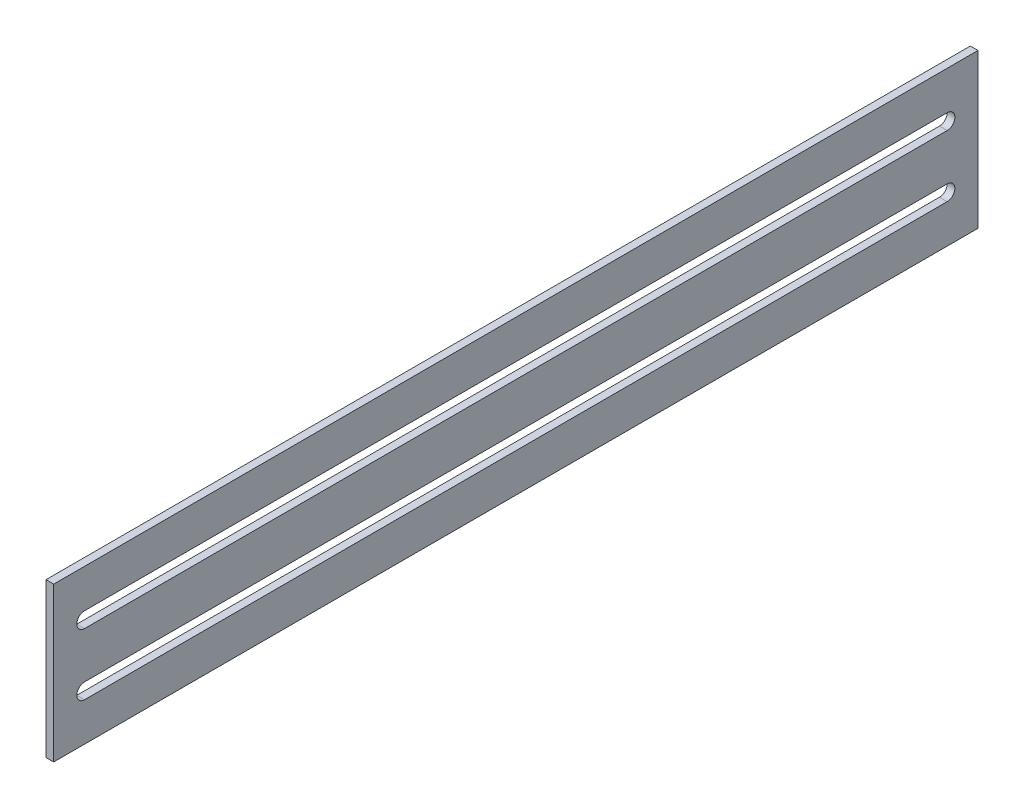
SolidWorks part; units mm, degrees
ref_plane "Front Plane" through (0, 0, 0) normal (0, 0, 1) x (1, 0, 0)
ref_plane "Top Plane" through (0, 0, 0) normal (0, 1, 0) x (1, 0, 0)
ref_plane "Right Plane" through (0, 0, 0) normal (1, 0, 0) x (0, 0, -1)
sketch "Sketch1" plane through (0, 0, 0) normal (1, 0, 0) x (0, 0, -1)
  line L1 (-190.5, -31.75) -> (190.5, -31.75)
  line L2 (-190.5, -31.75) -> (-190.5, 31.75)
  line L3 (-190.5, 31.75) -> (190.5, 31.75)
  line L4 (190.5, -31.75) -> (190.5, 31.75)
  line L5 (-190.5, -31.75) -> (190.5, 31.75) construction
  line L6 (-190.5, 31.75) -> (190.5, -31.75) construction
  point P0 (0, 0)
  dimension "D1" = 381
  dimension "D2" = 63.5
extrude "Outer Cut" add sketch "Sketch1" along normal mid plane 3.175
sketch "Sketch2" plane through (1.5875, 0, 0) normal (1, 0, 0) x (0, 0, -1)
  line L0 (-190.5, 0) -> (190.5, 0) construction
  line L1 (-190.5, 31.75) -> (-190.5, -31.75) construction
  line L2 (190.5, -31.75) -> (190.5, 31.75) construction
  line L3 (-177.8, 12.7) -> (177.8, 12.7) construction
  line L4 (-177.8, 15.875) -> (177.8, 15.875)
  line L5 (-177.8, 9.525) -> (177.8, 9.525)
  line L6 (-177.8, -12.7) -> (177.8, -12.7) construction
  line L7 (-177.8, -15.875) -> (177.8, -15.875)
  line L8 (-177.8, -9.525) -> (177.8, -9.525)
  arc A0 (-177.8, 15.875) -> (-177.8, 9.525) centre (-177.8, 12.7) ccw
  arc A1 (177.8, 9.525) -> (177.8, 15.875) centre (177.8, 12.7) ccw
  arc A2 (-177.8, -15.875) -> (-177.8, -9.525) centre (-177.8, -12.7) cw
  arc A3 (177.8, -9.525) -> (177.8, -15.875) centre (177.8, -12.7) cw
  point P2 (0, 12.7)
  point P16 (0, -12.7)
  dimension "D1" = 6.35
  dimension "D2" = 25.4
  dimension "D3" = 12.7
  dimension "D4" = 12.7
extrude "Slots" cut sketch "Sketch2" against normal through all
